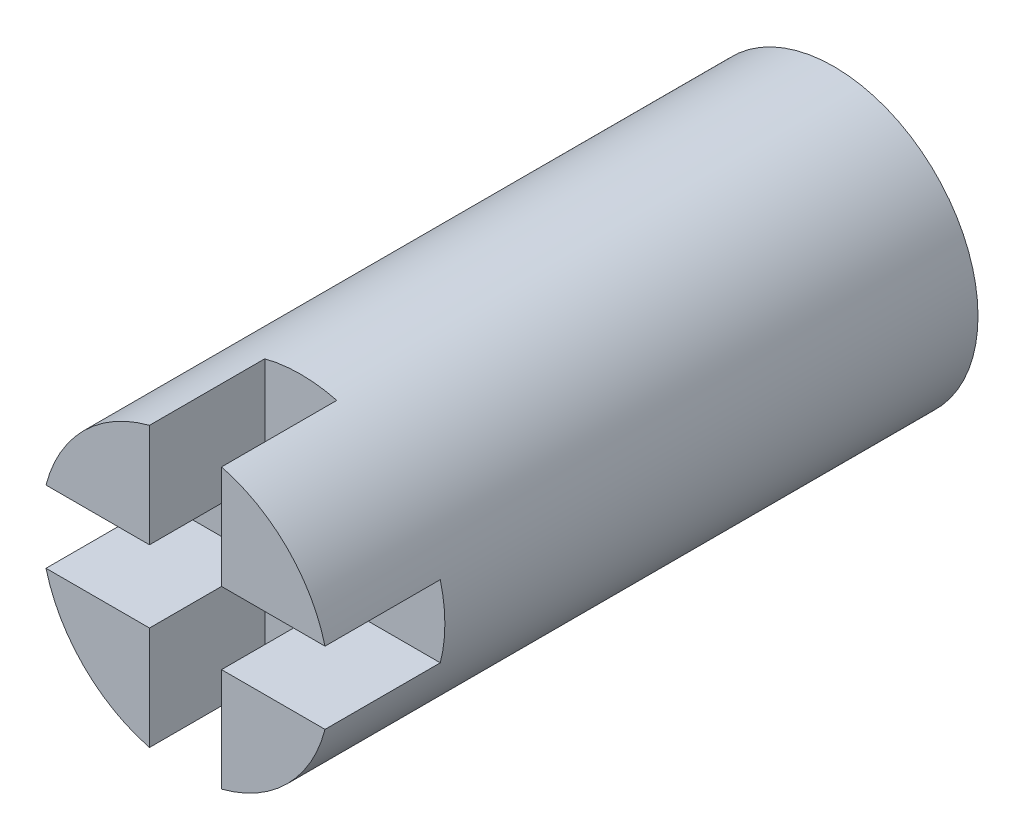
SolidWorks part; units mm, degrees
ref_plane "Front Plane" through (0, 0, 0) normal (0, 0, 1) x (1, 0, 0)
ref_plane "Top Plane" through (0, 0, 0) normal (0, 1, 0) x (1, 0, 0)
ref_plane "Right Plane" through (0, 0, 0) normal (1, 0, 0) x (0, 0, -1)
sketch "Sketch1" plane through (0, 0, 0) normal (0, 0, 1) x (1, 0, 0)
  circle A0 centre (0, 0) radius 6.35
  dimension "D1" = 12.7
extrude "Boss-Extrude1" add sketch "Sketch1" along normal blind 28.575
sketch "Sketch2" plane through (0, 0, 0) normal (0, 0, -1) x (-1, 0, 0)
  circle A0 centre (0, 0) radius 2.9464
  dimension "D1" = 5.8928
extrude "Cut-Extrude1" cut sketch "Sketch2" against normal blind 12.7 contours A0
sketch "Sketch4" plane through (0, 0, 28.575) normal (0, 0, 1) x (1, 0, 0)
  line L0 (-6.35, 0) -> (6.35, 0) construction
  line L1 (0, 6.35) -> (0, -6.35) construction
  line L3 (-1.5875, -6.6025) -> (1.5875, -6.6025)
  line L4 (-1.5875, -6.6025) -> (-1.5875, 6.6025)
  line L5 (-1.5875, 6.6025) -> (1.5875, 6.6025)
  line L6 (1.5875, -6.6025) -> (1.5875, 6.6025)
  line L7 (-1.5875, -6.6025) -> (1.5875, 6.6025) construction
  line L8 (-1.5875, 6.6025) -> (1.5875, -6.6025) construction
  line L9 (-7.6652, 1.5875) -> (7.6652, 1.5875)
  line L10 (-7.6652, 1.5875) -> (-7.6652, -1.5875)
  line L11 (-7.6652, -1.5875) -> (7.6652, -1.5875)
  line L12 (7.6652, 1.5875) -> (7.6652, -1.5875)
  line L13 (-7.6652, 1.5875) -> (7.6652, -1.5875) construction
  line L14 (-7.6652, -1.5875) -> (7.6652, 1.5875) construction
  circle A0 centre (0, 0) radius 6.35 construction
  point P7 (0, 0)
  point P12 (0, 0)
  circle M9 centre (0, 0) radius 6.35
  dimension "D1" = 3.175
extrude "Cut-Extrude2" cut sketch "Sketch4" against normal blind 5.08 contours L4 L9 L6 M9 | L4 L11 L6 L9 | L11 L4 L9 M9 | L6 L11 L9 M9 | L11 L4 L6 M9
